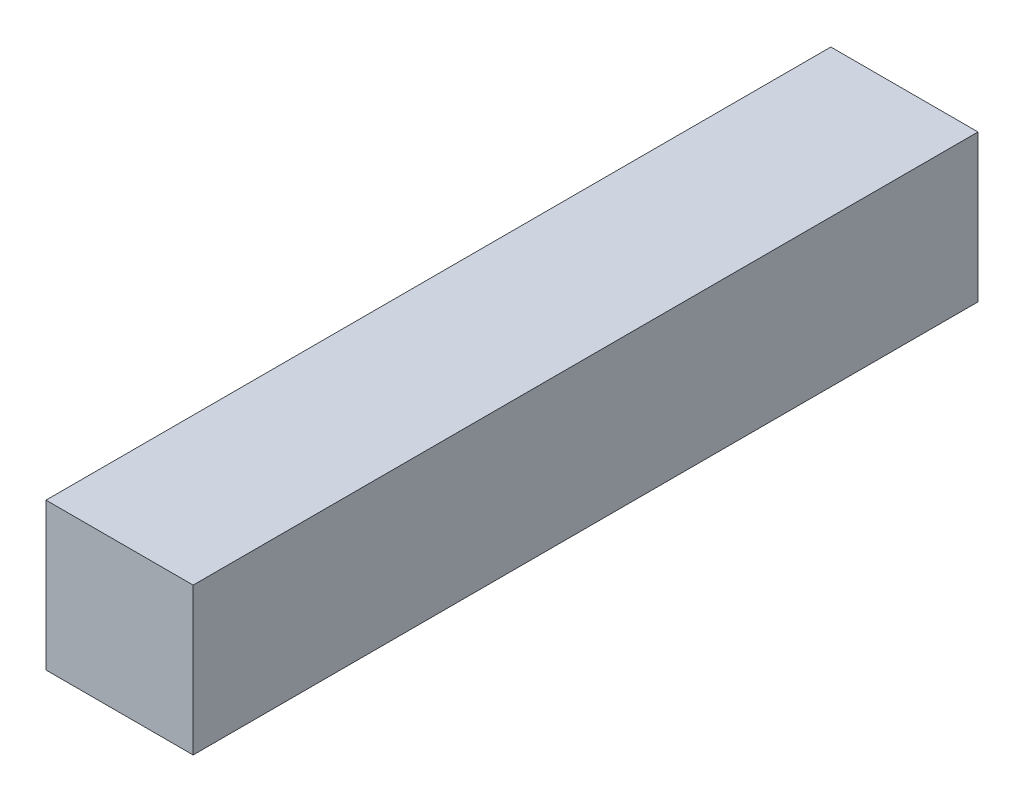
SolidWorks part; units mm, degrees
material "Cast Carbon Steel"
ref_plane "Front Plane" through (0, 0, 0) normal (0, 0, 1) x (1, 0, 0)
ref_plane "Top Plane" through (0, 0, 0) normal (0, 1, 0) x (1, 0, 0)
ref_plane "Right Plane" through (0, 0, 0) normal (1, 0, 0) x (0, 0, -1)
sketch "Sketch1" plane through (0, 0, 0) normal (0, 0, 1) x (1, 0, 0)
  line L1 (-2.3813, 2.3813) -> (2.3812, 2.3813)
  line L2 (-2.3813, 2.3813) -> (-2.3812, -2.3812)
  line L3 (-2.3812, -2.3812) -> (2.3813, -2.3812)
  line L4 (2.3812, 2.3813) -> (2.3813, -2.3812)
  line L5 (-2.3813, 2.3813) -> (2.3813, -2.3812) construction
  line L6 (-2.3812, -2.3812) -> (2.3812, 2.3813) construction
  point P0 (0, 0)
  dimension "D1" = 4.7625
  dimension "D2" = 4.7625
extrude "Boss-Extrude1" add sketch "Sketch1" along normal mid plane 25.4
